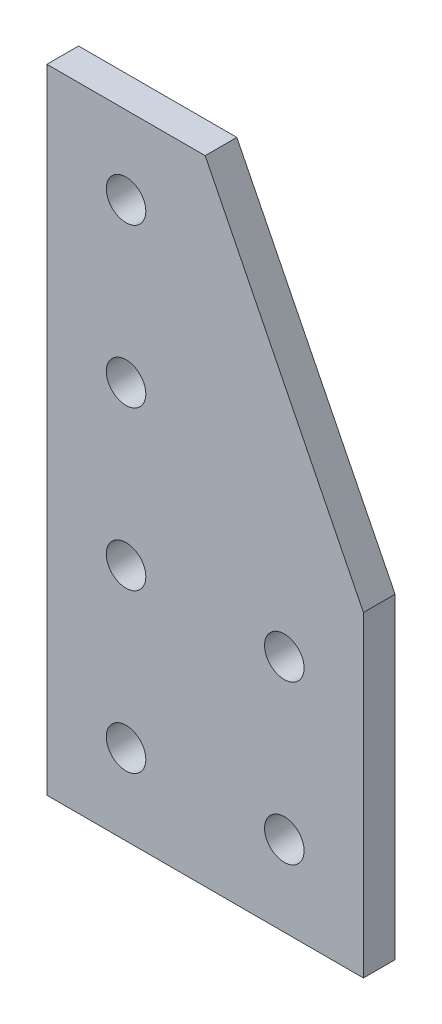
SolidWorks part; units mm, degrees
ref_plane "Front Plane" through (0, 0, 0) normal (0, 0, 1) x (1, 0, 0)
ref_plane "Top Plane" through (0, 0, 0) normal (0, 1, 0) x (1, 0, 0)
ref_plane "Right Plane" through (0, 0, 0) normal (1, 0, 0) x (0, 0, -1)
sketch "Sketch1" plane through (0, 0, 0) normal (0, 0, 1) x (1, 0, 0)
  line L0 (0, -40) -> (0, 40)
  line L1 (0, 40) -> (20, 40)
  line L2 (20, 40) -> (40, 0)
  line L3 (40, 0) -> (40, -40)
  line L4 (40, -40) -> (0, -40)
  line L5 (10, -29.84) -> (30, -29.84)
  line L6 (20, -40) -> (20, 40) construction
  circle A0 centre (10, -29.84) radius 2.5
  circle A1 centre (30, -29.84) radius 2.5
  circle A2 centre (10, -9.84) radius 2.5
  circle A3 centre (10, 10.16) radius 2.5
  circle A4 centre (10, 30.16) radius 2.5
  circle A5 centre (30, -9.84) radius 2.5
  point P4 (0, 0)
  point P12 (20, -40)
  point P13 (20, -29.84)
  dimension "D7" = 5
  dimension "D1" = 80
  dimension "D2" = 20
  dimension "D3" = 40
  dimension "D4" = 40
  dimension "D5" = 20
  dimension "D6" = 10.16
  dimension "D9" = 20
  dimension "D8" = 4
extrude "Boss-Extrude1" add sketch "Sketch1" along normal blind 4
